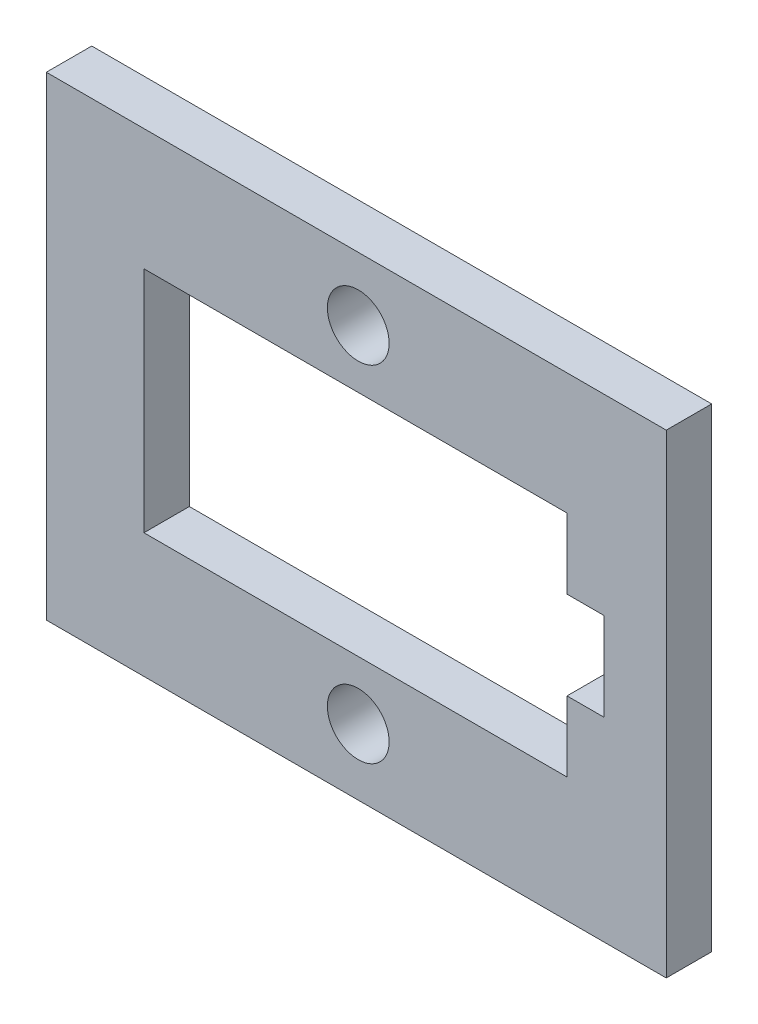
SolidWorks part; units mm, degrees
ref_plane "Front Plane" through (0, 0, 0) normal (0, 0, 1) x (1, 0, 0)
ref_plane "Top Plane" through (0, 0, 0) normal (0, 1, 0) x (1, 0, 0)
ref_plane "Right Plane" through (0, 0, 0) normal (1, 0, 0) x (0, 0, -1)
other "Graphic1"
other "Graphic (Closed) -1"
sketch "Sketch1" plane through (0, 0, 0) normal (0, 0, 1) x (1, 0, 0)
  line L0 (30.684, 15.5673) -> (28.6621, 15.5673)
  line L1 (34.1244, 26.1177) -> (0, 26.1177)
  line L2 (34.1244, 26.1177) -> (34.1244, 0)
  line L3 (34.1244, 0) -> (0, 0)
  line L4 (0, 26.1177) -> (0, 0)
  line L9 (28.6621, 15.5673) -> (28.6621, 19.4347)
  line L10 (28.6621, 19.4347) -> (5.3725, 19.4347)
  line L11 (5.3725, 19.4347) -> (5.3725, 6.85)
  line L12 (5.3725, 6.85) -> (28.6621, 6.85)
  line L13 (28.6621, 6.85) -> (28.6621, 10.7175)
  line L14 (28.6621, 10.7175) -> (30.684, 10.7175)
  line L15 (30.684, 10.7175) -> (30.684, 15.5673)
  circle A0 centre (17.17, 3.63) radius 1.7
  circle A1 centre (17.17, 22.63) radius 1.7
extrude "Boss-Extrude3" add sketch "Sketch1" along normal blind 2.5
